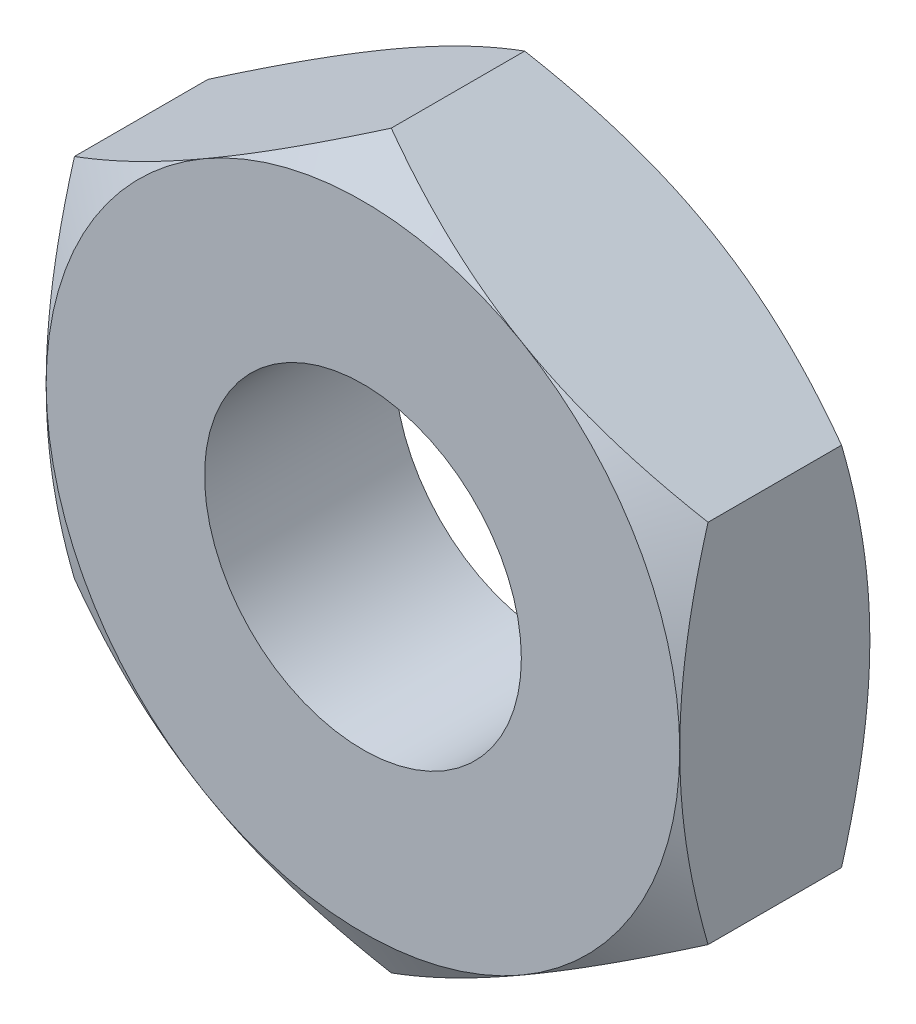
SolidWorks part; units mm, degrees
material "1.4000 (X6Cr13)"
ref_plane "Płaszczyzna przednia" through (0, 0, 0) normal (0, 0, 1) x (1, 0, 0)
ref_plane "Płaszczyzna górna" through (0, 0, 0) normal (0, 1, 0) x (1, 0, 0)
ref_plane "Płaszczyzna prawa" through (0, 0, 0) normal (1, 0, 0) x (0, 0, -1)
sketch "Szkic1" plane through (0, 0, 0) normal (0, 0, 1) x (1, 0, 0)
  line L1 (-2, 1.1547) -> (-2, -1.1547)
  line L2 (-2, -1.1547) -> (0, -2.3094)
  line L3 (0, -2.3094) -> (2, -1.1547)
  line L4 (2, -1.1547) -> (2, 1.1547)
  line L5 (2, 1.1547) -> (0, 2.3094)
  line L6 (0, 2.3094) -> (-2, 1.1547)
  circle A0 centre (0, 0) radius 1
  circle A1 centre (0, 0) radius 2 construction
  dimension "d" = 2
  dimension "s" = 4
extrude "Dodanie-wyciągnięcie1" add sketch "Szkic1" along normal mid plane 1.2
sketch "Szkic2" plane through (0, 0, 0.6) normal (0, 0, 1) x (1, 0, 0)
  circle A0 centre (0, 0) radius 2
  dimension "D1" = 4
extrude "Wytnij-wyciągnięcie2" cut sketch "Szkic2" against normal blind 1.2 draft 60 flip side to cut
mirror "Lustro1" about plane through (0, 0, 0) normal (0, 0, 1) of "Wytnij-wyciągnięcie2"
equation "\"D1@Szkic2\" = \"s@Szkic1\""
equation "\"D1@Wytnij-wyciągnięcie2\" = \"m@Dodanie-wyciągnięcie1\""
